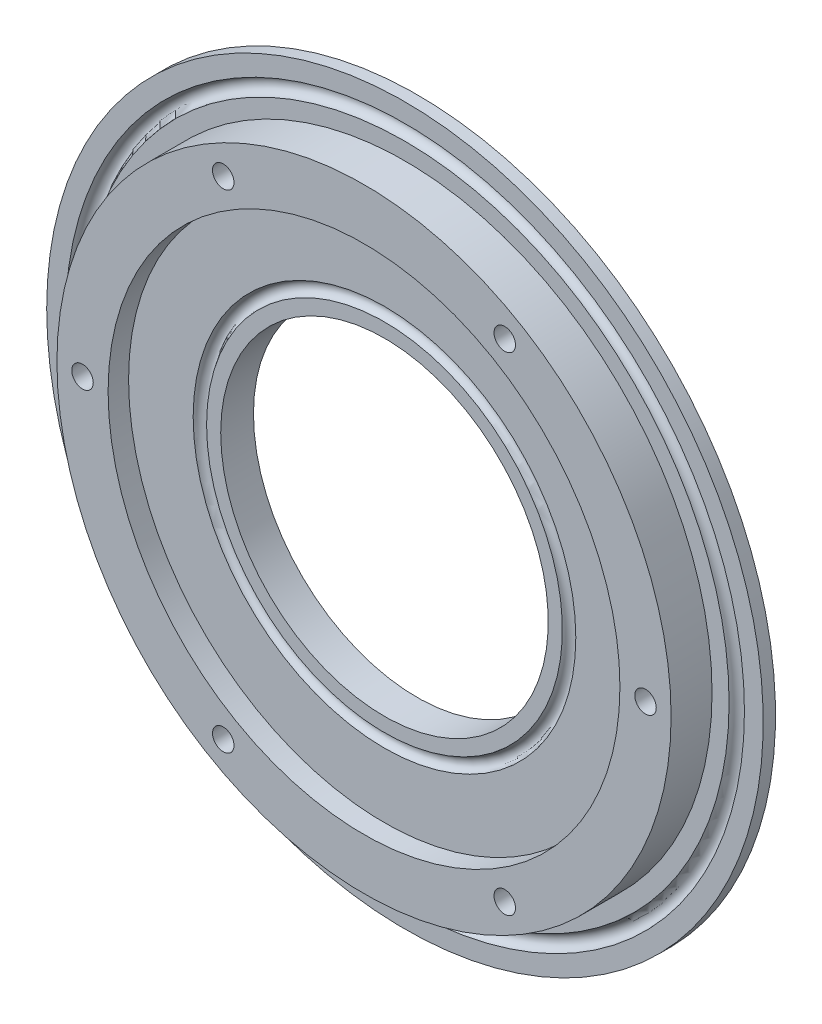
SolidWorks part; units mm, degrees
ref_plane "Plano frontal" through (0, 0, 0) normal (0, 0, 1) x (1, 0, 0)
ref_plane "Plano superior" through (0, 0, 0) normal (0, 1, 0) x (1, 0, 0)
ref_plane "Plano direito" through (0, 0, 0) normal (1, 0, 0) x (0, 0, -1)
sketch "Esboço2" plane through (0, 0, 0) normal (0, 1, 0) x (1, 0, 0)
  line L0 (-882.7991, 2) -> (49117.2009, 2) construction
  line L1 (-1091.976, -2) -> (48908.024, -2) construction
  line L2 (-66.33, 2) -> (-70, 2)
  line L3 (-70, 2) -> (-70, 4.4)
  line L4 (-70, 4.4) -> (-32, 4.4)
  line L5 (-32, 4.4) -> (-32, -2)
  line L8 (-32, -2) -> (-34.76, -2)
  line L9 (-37.38, -2) -> (-50, -2)
  line L10 (-50, -2) -> (-50, -6)
  line L11 (-50, -6) -> (-60, -6)
  line L12 (-60, -6) -> (-60, 2)
  line L13 (-60, 2) -> (-63.33, 2)
  circle A0 centre (-64.83, 2) radius 1.5 construction
  circle A1 centre (-36.07, -2) radius 1.31 construction
  arc A2 (-34.76, -2) -> (-37.38, -2) centre (-36.07, -2.1622) ccw
  arc A3 (-63.33, 2) -> (-66.33, 2) centre (-64.83, 2) ccw
  point P9 (-34.76, -2)
  point P12 (-63.33, 2)
  dimension "D4" = 2.62
  dimension "D5" = 3
  dimension "D3" = 34.76
  dimension "D7" = 50
  dimension "D1" = 2
  dimension "D2" = 2
  dimension "D6" = 63.33
  dimension "D8" = 60
  dimension "D9" = 70
  dimension "D10" = 32
  dimension "D11" = 2.4
  dimension "D12" = 4
ref_axis "Eixo1" through (0, 0, -4.826) along (0, 0, 1)
revolve "Revolução1" add sketch "Esboço2" angle 360 about axis through (0, 0, -4.826) along (0, 0, 1)
sketch "Esboço5" plane through (0, 0, 2) normal (0, 0, 1) x (1, 0, 0)
  line L1 (27.5, 47.6314) -> (-27.5, 47.6314)
  line L2 (-27.5, 47.6314) -> (-55, 0)
  line L3 (-55, 0) -> (-27.5, -47.6314)
  line L4 (-27.5, -47.6314) -> (27.5, -47.6314)
  line L5 (27.5, -47.6314) -> (55, 0)
  line L6 (55, 0) -> (27.5, 47.6314)
  circle A0 centre (0, 0) radius 55 construction
  dimension "D1" = 110
hole_wizard "Broca de rosquear para tarraxa de M5x0.81" positions "Esboço7" profile "Esboço6" hole size "M5x0.8" standard "Métrico Ansi"
sketch "Esboço7" plane through (0, 0, 6) normal (0, 0, 1) x (1, 0, 0)
  point P0 (-27.5, 47.6314)
  point P1 (27.5, 47.6314)
  point P4 (55, 0)
  point P7 (27.5, -47.6314)
  point P10 (-27.5, -47.6314)
  point P13 (-55, 0)
sketch "Esboço6" plane through (-27.5, 47.6314, 6) normal (1, 0, 0) x (0, -1, 0)
  line L0 (0, 0) -> (0, 8.2618)
  line L1 (0, 8.2618) -> (2.1, 7)
  line L2 (2.1, 7) -> (2.1, 0)
  line L5 (2.1, 0) -> (0, 0)
  line L10 (0, 8.2618) -> (-2.1, 7) construction
  line L11 (0, -6.35) -> (0, 107.95) construction
  dimension "Hole Dia." = 4.2
  dimension "Hole Depth" = 7
  dimension "Drill Angle" = 118
cosmetic thread "Representação de rosca1" parameters "D2"=5
cosmetic thread "Representação de rosca2" parameters "D2"=5
cosmetic thread "Representação de rosca3" parameters "D2"=5
cosmetic thread "Representação de rosca4" parameters "D2"=5
cosmetic thread "Representação de rosca5" parameters "D2"=5
cosmetic thread "Representação de rosca6" parameters "D2"=5
